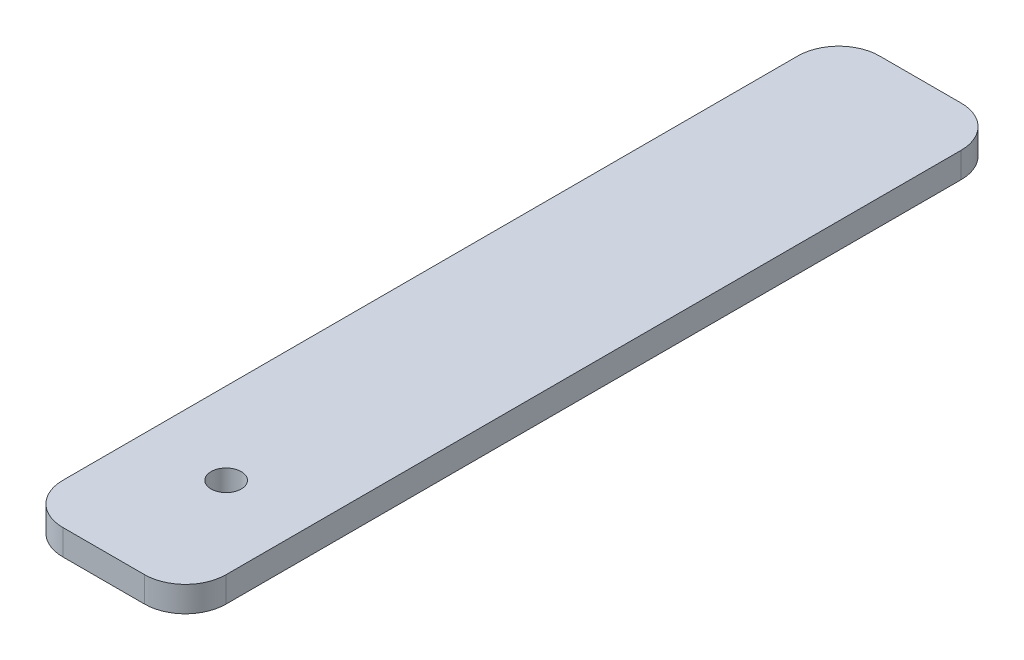
SolidWorks part; units mm, degrees
ref_plane "Front Plane" through (0, 0, 0) normal (0, 0, 1) x (1, 0, 0)
ref_plane "Top Plane" through (0, 0, 0) normal (0, 1, 0) x (1, 0, 0)
ref_plane "Right Plane" through (0, 0, 0) normal (1, 0, 0) x (0, 0, -1)
sketch "Sketch1" plane through (0, 0, 0) normal (0, 1, 0) x (1, 0, 0)
  line L0 (5.08, 0) -> (5.08, 50.8) construction
  line L1 (0, 0) -> (10.16, 0)
  line L2 (0, 0) -> (0, 50.8)
  line L3 (0, 50.8) -> (10.16, 50.8)
  line L4 (10.16, 0) -> (10.16, 50.8)
  circle A0 centre (5.08, 7.62) radius 0.9398
  dimension "D1" = 1.8796
  dimension "D2" = 7.62
  dimension "D3" = 50.8
  dimension "D4" = 10.16
extrude "Boss-Extrude1" add sketch "Sketch1" along normal blind 1.5875
fillet "Fillet1" radius 2.54 4 edges at (0, 0.7937, -50.8) (10.16, 0.7937, -50.8) (10.16, 0.7937, 0) (0, 0.7937, 0)
